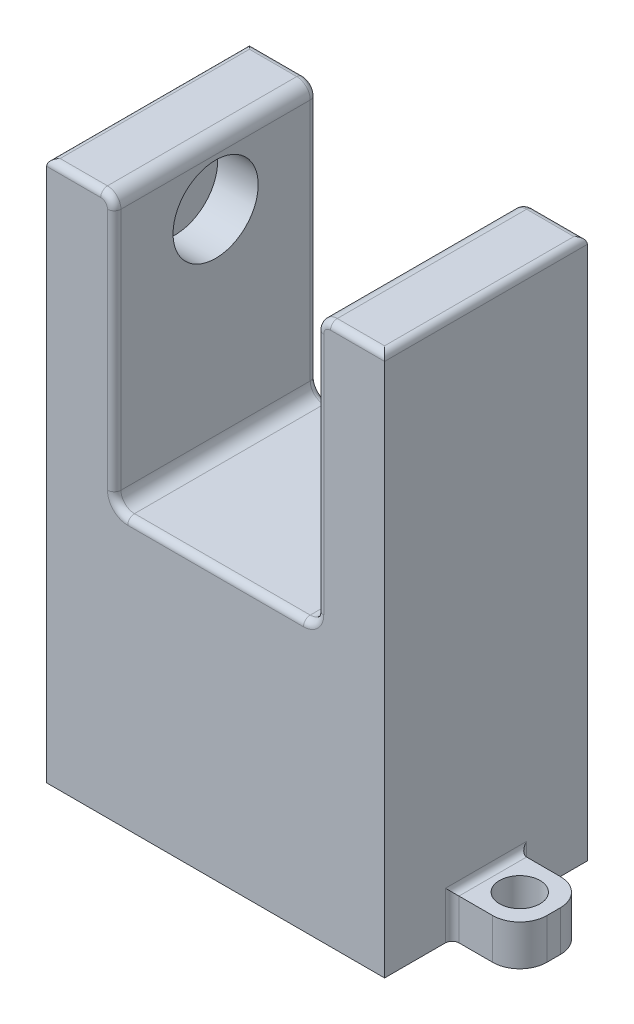
SolidWorks part; units mm, degrees
ref_plane "Alzado" through (0, 0, 0) normal (0, 0, 1) x (1, 0, 0)
ref_plane "Planta" through (0, 0, 0) normal (0, 1, 0) x (1, 0, 0)
ref_plane "Vista lateral" through (0, 0, 0) normal (1, 0, 0) x (0, 0, -1)
sketch "Croquis2" plane through (0, 0, 0) normal (0, 1, 0) x (1, 0, 0)
  line L1 (-12.5, 7.5) -> (12.5, 7.5)
  line L2 (-12.5, 7.5) -> (-12.5, -7.5)
  line L3 (-12.5, -7.5) -> (12.5, -7.5)
  line L4 (12.5, 7.5) -> (12.5, -7.5)
  line L5 (-12.5, 7.5) -> (12.5, -7.5) construction
  line L6 (-12.5, -7.5) -> (12.5, 7.5) construction
  point P0 (0, 0)
  dimension "D1" = 25
  dimension "D2" = 15
extrude "Saliente-Extruir1" add sketch "Croquis2" along normal blind 40
sketch "Croquis3" plane through (0, 40, 0) normal (0, 1, 0) x (1, 0, 0)
  line L0 (-12.5, -7.5) -> (12.5, -7.5) construction
  line L1 (-7.5, 7.5) -> (7.5, 7.5)
  line L2 (-7.5, 7.5) -> (-7.5, -7.5)
  line L3 (-7.5, -7.5) -> (7.5, -7.5)
  line L4 (7.5, 7.5) -> (7.5, -7.5)
  line L5 (-7.5, 7.5) -> (7.5, -7.5) construction
  line L6 (-7.5, -7.5) -> (7.5, 7.5) construction
  point P0 (0, 0)
  dimension "D1" = 5
extrude "Cortar-Extruir1" cut sketch "Croquis3" against normal blind 20
fillet "Redondeo1" radius 1 2 edges at (7.5, 20, 0) (-7.5, 20, 0)
fillet "Redondeo2" radius 1 2 edges at (-7.5, 40, 0) (7.5, 40, 0)
sketch "Croquis4" plane through (-7.5, 0, 0) normal (1, 0, 0) x (0, 0, -1)
  line L0 (0, 40) -> (0, 20) construction
  line L1 (-7.5, 40) -> (7.5, 40) construction
  circle A0 centre (0, 35.5) radius 3.15
  dimension "D2" = 6.3
  dimension "D1" = 20
  dimension "D3" = 4.5
extrude "Cortar-Extruir2" cut sketch "Croquis4" against normal blind 3 and the other way blind 18 from surface at 0 starting at face at (-7.5, 30, 0)
sketch "Croquis6" plane through (12.5, 0, 0) normal (1, 0, 0) x (0, 0, -1)
  line L0 (-2.5, 0) -> (2.5, 0)
  line L1 (-7.5, 0) -> (7.5, 0) construction
  line L2 (-2.5, 0) -> (-2.5, 3)
  line L3 (-2.5, 3) -> (2.5, 3)
  line L4 (2.5, 3) -> (2.5, 0)
  point P6 (0, 0)
  dimension "D1" = 5
  dimension "D2" = 3
extrude "Saliente-Extruir2" add sketch "Croquis6" along normal blind 5
fillet "Redondeo3" radius 2 2 edges at (17.5, 1.5, 2.5) (17.5, 1.5, -2.5)
sketch "Croquis8" plane through (0, 3, 0) normal (0, 1, 0) x (1, 0, 0)
  line L0 (17.5, 0) -> (12.5, 0) construction
  line L1 (17.5, 0.5) -> (17.5, -0.5) construction
  line L2 (12.5, 2.5) -> (12.5, -2.5) construction
  circle A0 centre (15, 0) radius 1.5
  dimension "D1" = 3
extrude "Cortar-Extruir3" cut sketch "Croquis8" against normal blind 15
sketch "Croquis9" plane through (-12.5, 0, 0) normal (-1, 0, 0) x (0, 0, 1)
  line L0 (-2.5, 0) -> (2.5, 0)
  line L1 (-2.5, 0) -> (-2.5, 3)
  line L2 (-2.5, 3) -> (2.5, 3)
  line L3 (2.5, 3) -> (2.5, 0)
  point P4 (0, 0)
  dimension "D1" = 5
  dimension "D2" = 3
extrude "Saliente-Extruir3" add sketch "Croquis9" along normal blind 5
sketch "Croquis10" plane through (0, 3, 0) normal (0, 1, 0) x (1, 0, 0)
  line L0 (-17.5, 0) -> (-12.5, 0) construction
  line L1 (-17.5, -2.5) -> (-17.5, 2.5) construction
  line L2 (-12.5, 7.5) -> (-12.5, -7.5) construction
  circle A0 centre (-15, 0) radius 1.5
  dimension "D1" = 3
extrude "Cortar-Extruir4" cut sketch "Croquis10" against normal up to next
fillet "Redondeo4" radius 2 2 edges at (-17.5, 1.5, -2.5) (-17.5, 1.5, 2.5)
fillet "Redondeo5" radius 0.5 6 edges at (-12.5, 3, 0) (-12.5, 1.5, 2.5) (-12.5, 1.5, -2.5) (12.5, 1.5, -2.5) (12.5, 1.5, 2.5) (12.5, 3, 0)
fillet "Redondeo6" radius 0.5 20 edges at (10.5, 40, -7.5) (7.7929, 39.7071, -7.5) (7.5, 30, -7.5) (7.2071, 20.2929, -7.5) (-10.5, 40, -7.5) (-7.7929, 39.7071, -7.5) (-7.5, 30, -7.5) (-7.2071, 20.2929, -7.5) (-10.5, 40, 7.5) (-7.7929, 39.7071, 7.5) (-7.5, 30, 7.5) (-7.2071, 20.2929, 7.5) (10.5, 40, 7.5) (7.7929, 39.7071, 7.5) (7.5, 30, 7.5) (7.2071, 20.2929, 7.5) (-12.5, 40, 0) (12.5, 40, 0) (0, 20, -7.5) (0, 20, 7.5)
